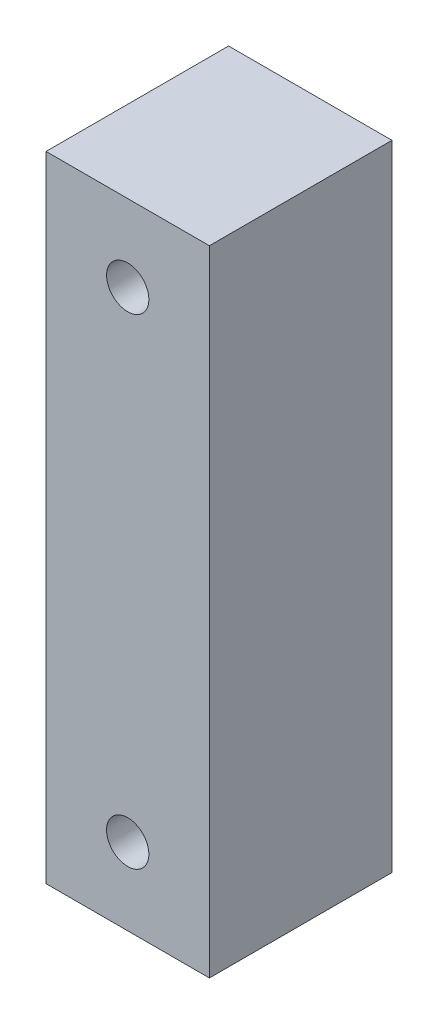
SolidWorks part; units mm, degrees
ref_plane "Front Plane" through (0, 0, 0) normal (1, 0, 0) x (0, 1, 0)
ref_plane "Top Plane" through (0, 0, 0) normal (0, 0, 1) x (0, 1, 0)
ref_plane "Right Plane" through (0, 0, 0) normal (0, 1, 0) x (-1, 0, 0)
sketch "Sketch1" plane through (0, 0, 0) normal (1, 0, 0) x (0, 1, 0)
  line L0 (-165, -83.5) -> (165, -83.5)
  line L1 (165, -83.5) -> (165, 11.5)
  line L4 (0, 11.5) -> (0, -83.5) construction
  line L5 (-165, -83.5) -> (-165, 11.5)
  line L8 (-165, 11.5) -> (165, 11.5)
  point P15 (0, -83.5)
  dimension "D1" = 95
  dimension "D4" = 165
extrude "Boss-Extrude1" add sketch "Sketch1" along normal blind 85
sketch "Sketch3" plane through (0, 0, 11.5) normal (0, 0, 1) x (1, 0, 0)
  line L0 (0, 0) -> (85, 0) construction
  line L1 (42.5, 0) -> (42.5, 125) construction
  line L2 (0, 165) -> (0, -165) construction
  line L3 (85, 165) -> (85, -165) construction
  circle A0 centre (42.5, 125) radius 11
  circle A1 centre (42.5, -125) radius 11
  point P4 (42.5, 0)
  dimension "D2" = 22
  dimension "D1" = 125
extrude "Cut-Extrude2" cut sketch "Sketch3" against normal blind 150
